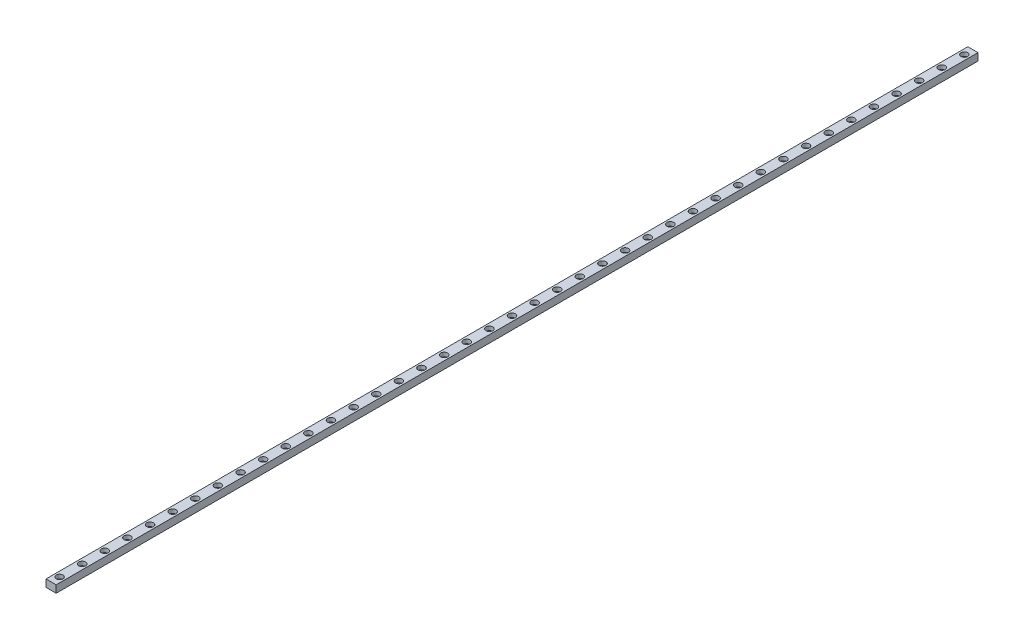
SolidWorks part; units mm, degrees
material "AISI 304"
ref_plane "前视基准面" through (0, 0, 0) normal (0, 0, 1) x (1, 0, 0)
ref_plane "上视基准面" through (0, 0, 0) normal (0, 1, 0) x (1, 0, 0)
ref_plane "右视基准面" through (0, 0, 0) normal (1, 0, 0) x (0, 0, -1)
sketch "草图1" plane through (0, 0, -89.2648) normal (0, 0, 1) x (1, 0, 0)
  line L1 (-4.5, -3.25) -> (4.5, -3.25)
  line L2 (-4.5, -3.25) -> (-4.5, 3.25)
  line L3 (-4.5, 3.25) -> (4.5, 3.25)
  line L4 (4.5, -3.25) -> (4.5, 3.25)
  line L5 (-4.5, -3.25) -> (4.5, 3.25) construction
  line L6 (-4.5, 3.25) -> (4.5, -3.25) construction
  point P0 (0, 0)
  dimension "D1" = 9
  dimension "D2" = 6.5
extrude "凸台-拉伸1" add sketch "草图1" along normal blind 815
sketch "草图2" plane through (0, 3.25, 0) normal (0, 1, 0) x (1, 0, 0)
  line L0 (0, 0) -> (0, -499.5684) construction
  line L1 (4.5, 89.2648) -> (-4.5, 89.2648) construction
  circle A0 centre (0, 81.7648) radius 1.75
  circle A1 centre (0, 61.7648) radius 1.75
  circle A2 centre (0, 41.7648) radius 1.75
  circle A3 centre (0, 21.7648) radius 1.75
  circle A4 centre (0, 1.7648) radius 1.75
  circle A5 centre (0, -18.2352) radius 1.75
  circle A6 centre (0, -38.2352) radius 1.75
  circle A7 centre (0, -58.2352) radius 1.75
  circle A8 centre (0, -78.2352) radius 1.75
  circle A9 centre (0, -98.2352) radius 1.75
  circle A10 centre (0, -118.2352) radius 1.75
  circle A11 centre (0, -138.2352) radius 1.75
  circle A12 centre (0, -158.2352) radius 1.75
  circle A13 centre (0, -178.2352) radius 1.75
  circle A14 centre (0, -198.2352) radius 1.75
  circle A15 centre (0, -218.2352) radius 1.75
  circle A16 centre (0, -238.2352) radius 1.75
  circle A17 centre (0, -258.2352) radius 1.75
  circle A18 centre (0, -278.2352) radius 1.75
  circle A19 centre (0, -298.2352) radius 1.75
  circle A20 centre (0, -318.2352) radius 1.75
  circle A21 centre (0, -338.2352) radius 1.75
  circle A22 centre (0, -358.2352) radius 1.75
  circle A23 centre (0, -378.2352) radius 1.75
  circle A24 centre (0, -398.2352) radius 1.75
  circle A25 centre (0, -418.2352) radius 1.75
  circle A26 centre (0, -438.2352) radius 1.75
  circle A27 centre (0, -458.2352) radius 1.75
  circle A28 centre (0, -478.2352) radius 1.75
  circle A29 centre (0, -498.2352) radius 1.75
  circle A30 centre (0, -518.2352) radius 1.75
  circle A31 centre (0, -538.2352) radius 1.75
  circle A32 centre (0, -558.2352) radius 1.75
  circle A33 centre (0, -578.2352) radius 1.75
  circle A34 centre (0, -598.2352) radius 1.75
  circle A35 centre (0, -618.2352) radius 1.75
  circle A36 centre (0, -638.2352) radius 1.75
  circle A37 centre (0, -658.2352) radius 1.75
  circle A38 centre (0, -678.2352) radius 1.75
  circle A39 centre (0, -698.2352) radius 1.75
  circle A40 centre (0, -718.2352) radius 1.75
  circle A41 centre (0, -738.2352) radius 1.75
  circle A42 centre (0, -758.2352) radius 1.75
  circle A43 centre (0, -778.2352) radius 1.75
  circle A44 centre (0, -798.2352) radius 1.75
  circle A45 centre (0, -818.2352) radius 1.75
  circle A46 centre (0, -838.2352) radius 1.75
  circle A47 centre (0, -858.2352) radius 1.75
  circle A48 centre (0, -878.2352) radius 1.75
  circle A49 centre (0, -898.2352) radius 1.75
  circle A50 centre (0, -918.2352) radius 1.75
  circle A51 centre (0, -938.2352) radius 1.75
  circle A52 centre (0, -958.2352) radius 1.75
  circle A53 centre (0, -978.2352) radius 1.75
  circle A54 centre (0, -998.2352) radius 1.75
  circle A55 centre (0, -1018.2352) radius 1.75
  circle A56 centre (0, -1038.2352) radius 1.75
  circle A57 centre (0, -1058.2352) radius 1.75
  circle A58 centre (0, -1078.2352) radius 1.75
  circle A59 centre (0, -1098.2352) radius 1.75
  dimension "D1" = 3.5
  dimension "D2" = 7.5
  dimension "D4" = 20
  dimension "D3" = 60
extrude "切除-拉伸1" cut sketch "草图2" against normal through all
sketch "草图3" plane through (0, 3.25, 0) normal (0, 1, 0) x (1, 0, 0)
  circle A0 centre (0, 81.7648) radius 3
  circle A1 centre (0, 61.7648) radius 3
  circle A2 centre (0, 41.7648) radius 3
  circle A3 centre (0, 21.7648) radius 3
  circle A4 centre (0, 1.7648) radius 3
  circle A5 centre (0, -18.2352) radius 3
  circle A6 centre (0, -38.2352) radius 3
  circle A7 centre (0, -58.2352) radius 3
  circle A8 centre (0, -78.2352) radius 3
  circle A9 centre (0, -98.2352) radius 3
  circle A10 centre (0, -118.2352) radius 3
  circle A11 centre (0, -138.2352) radius 3
  circle A12 centre (0, -158.2352) radius 3
  circle A13 centre (0, -178.2352) radius 3
  circle A14 centre (0, -198.2352) radius 3
  circle A15 centre (0, -218.2352) radius 3
  circle A16 centre (0, -238.2352) radius 3
  circle A17 centre (0, -258.2352) radius 3
  circle A18 centre (0, -278.2352) radius 3
  circle A19 centre (0, -298.2352) radius 3
  circle A20 centre (0, -318.2352) radius 3
  circle A21 centre (0, -338.2352) radius 3
  circle A22 centre (0, -358.2352) radius 3
  circle A23 centre (0, -378.2352) radius 3
  circle A24 centre (0, -398.2352) radius 3
  circle A25 centre (0, -418.2352) radius 3
  circle A26 centre (0, -438.2352) radius 3
  circle A27 centre (0, -458.2352) radius 3
  circle A28 centre (0, -478.2352) radius 3
  circle A29 centre (0, -498.2352) radius 3
  circle A30 centre (0, -518.2352) radius 3
  circle A31 centre (0, -538.2352) radius 3
  circle A32 centre (0, -558.2352) radius 3
  circle A33 centre (0, -578.2352) radius 3
  circle A34 centre (0, -598.2352) radius 3
  circle A35 centre (0, -618.2352) radius 3
  circle A36 centre (0, -638.2352) radius 3
  circle A37 centre (0, -658.2352) radius 3
  circle A38 centre (0, -678.2352) radius 3
  circle A39 centre (0, -698.2352) radius 3
  circle A40 centre (0, -718.2352) radius 3
  circle A41 centre (0, -738.2352) radius 3
  circle A42 centre (0, -758.2352) radius 3
  circle A43 centre (0, -778.2352) radius 3
  circle A44 centre (0, -798.2352) radius 3
  circle A45 centre (0, -818.2352) radius 3
  circle A46 centre (0, -838.2352) radius 3
  circle A47 centre (0, -858.2352) radius 3
  circle A48 centre (0, -878.2352) radius 3
  circle A49 centre (0, -898.2352) radius 3
  circle A50 centre (0, -918.2352) radius 3
  circle A51 centre (0, -938.2352) radius 3
  circle A52 centre (0, -958.2352) radius 3
  circle A53 centre (0, -978.2352) radius 3
  circle A54 centre (0, -998.2352) radius 3
  circle A55 centre (0, -1018.2352) radius 3
  circle A56 centre (0, -1038.2352) radius 3
  circle A57 centre (0, -1058.2352) radius 3
  circle A58 centre (0, -1078.2352) radius 3
  circle A59 centre (0, -1098.2352) radius 3
  dimension "D1" = 6
  dimension "D3" = 20
  dimension "D2" = 60
extrude "切除-拉伸2" cut sketch "草图3" against normal blind 3.5
